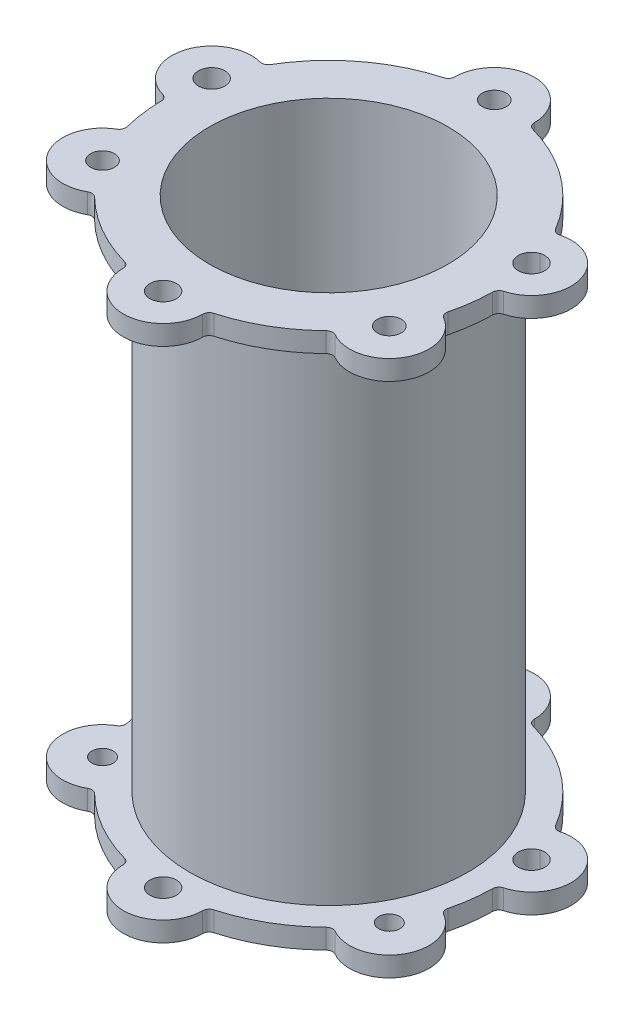
SolidWorks part; units mm, degrees
material "6061-T6 (SS)"
ref_plane "Front" through (0, 0, 0) normal (0, 0, 1) x (1, 0, 0)
ref_plane "Top" through (0, 0, 0) normal (0, 1, 0) x (1, 0, 0)
ref_plane "Right" through (0, 0, 0) normal (1, 0, 0) x (0, 0, -1)
sketch "Sketch1" plane through (0, 0, 0) normal (0, 1, 0) x (1, 0, 0)
  circle A0 centre (0, 0) radius 9
  circle A1 centre (0, 0) radius 10.5
  dimension "D1" = 18
  dimension "D2" = 21
extrude "Boss-Extrude1" add sketch "Sketch1" along normal blind 37.5
sketch "Sketch2" plane through (0, 37.5, 0) normal (0, 1, 0) x (1, 0, 0)
  line L0 (0, 10.5) -> (0, 12.5) construction
  line L1 (0, 0) -> (0, -12.5) construction
  line L2 (3, 0) -> (3, -12.5)
  line L3 (-3, 0) -> (-3, -12.5)
  line L4 (0, 0) -> (0, 12.5) construction
  line L7 (-3, 0) -> (-3, 12.5)
  line L10 (3, 0) -> (3, 12.5)
  line L11 (-1.5, -2.5981) -> (9.3253, -8.8481)
  line L12 (1.5, 2.5981) -> (12.3253, -3.6519)
  line L13 (0, 0) -> (10.8253, -6.25) construction
  line L14 (-1.5, 2.5981) -> (-12.3253, -3.6519)
  line L15 (1.5, -2.5981) -> (-9.3253, -8.8481)
  line L16 (0, 0) -> (-10.8253, -6.25) construction
  line L17 (0, 0) -> (-12.0741, 3.2352) construction
  line L18 (-0.7765, -2.8978) -> (-12.8505, 0.3375)
  line L19 (0.7765, 2.8978) -> (-11.2976, 6.133)
  line L20 (0, 36.7398) -> (0, -36.7398) construction
  line L21 (0, 0) -> (12.0741, 3.2352) construction
  line L22 (0.7765, -2.8978) -> (12.8505, 0.3375)
  line L23 (-0.7765, 2.8978) -> (11.2976, 6.133)
  circle A0 centre (0, 0) radius 9 construction
  circle A1 centre (0, 0) radius 9
  circle A2 centre (0, 0) radius 12.5
  circle A3 centre (0, 0) radius 10.5 construction
  arc A4 (3, 0) -> (-3, 0) centre (0, 0) ccw
  arc A5 (-3, -12.5) -> (3, -12.5) centre (0, -12.5) ccw
  circle A16 centre (0, -12.5) radius 1
  arc A22 (-3, 0) -> (3, 0) centre (0, 0) ccw
  arc A23 (3, 12.5) -> (-3, 12.5) centre (0, 12.5) ccw
  arc A25 (1.5, 2.5981) -> (-1.5, -2.5981) centre (0, 0) ccw
  arc A26 (9.3253, -8.8481) -> (12.3253, -3.6519) centre (10.8253, -6.25) ccw
  arc A28 (1.5, -2.5981) -> (-1.5, 2.5981) centre (0, 0) ccw
  arc A29 (-12.3253, -3.6519) -> (-9.3253, -8.8481) centre (-10.8253, -6.25) ccw
  arc A31 (-0.7765, -2.8978) -> (0.7765, 2.8978) centre (0, 0) ccw
  arc A32 (-11.2976, 6.133) -> (-12.8505, 0.3375) centre (-12.0741, 3.2352) ccw
  arc A33 (0.7765, -2.8978) -> (-0.7765, 2.8978) centre (0, 0) cw
  arc A34 (11.2976, 6.133) -> (12.8505, 0.3375) centre (12.0741, 3.2352) cw
  circle A35 centre (-12.0741, 3.2352) radius 1
  circle A36 centre (12.0741, 3.2352) radius 1
  point P8 (0, 11.5)
  point P10 (0, -6.25)
  point P19 (0, 6.25)
  point P29 (-6.037, 1.6176)
  point P31 (5.4127, -3.125)
  point P39 (-5.4127, -3.125)
  point P52 (6.037, 1.6176)
  point P55 (0, 0)
  dimension "D1" = 25
  dimension "D3" = 3
  dimension "D5" = 2
  dimension "D7" = 75
  dimension "D2" = 12.5
  dimension "D6" = 3
extrude "Boss-Extrude2" add sketch "Sketch2" along normal blind 1.5
ref_plane "Plane1" through (0, 18.75, 0) normal (0, -1, 0) x (-1, 0, 0)
fillet "Fillet1" radius 0.5 12 edges at (-3, 38.25, 12.1347) (3, 38.25, 12.1347) (9.0089, 38.25, 8.6654) (12.0089, 38.25, 3.4693) (12.4976, 38.25, -0.2429) (10.9447, 38.25, -6.0385) (3, 38.25, -12.1347) (-3, 38.25, -12.1347) (-10.9447, 38.25, -6.0385) (-12.4976, 38.25, -0.2429) (-12.0089, 38.25, 3.4693) (-9.0089, 38.25, 8.6654)
mirror "Mirror1" about plane through (0, 18.75, 0) normal (0, -1, 0) of "Boss-Extrude2", "Fillet1"
sketch "Sketch10" plane through (0, 0, 0) normal (0, 0, 1) x (1, 0, 0)
  line L0 (0, 0) -> (0, 10.55) construction
  circle A0 centre (0, 10.55) radius 7.65
  dimension "D2" = 15.3
  dimension "D1" = 10.55
extrude "Cut-Extrude1" cut sketch "Sketch10" against normal through all
sketch "Sketch11" plane through (0, -1.5, 0) normal (0, -1, 0) x (1, 0, 0)
  line L0 (0, 0) -> (0, -12.5) construction
  line L1 (0, 0) -> (-10.8253, 6.25) construction
  line L2 (0, 0) -> (10.8253, 6.25) construction
  dimension "D2" = 12.5
  dimension "D1" = 3
sketch "Sketch13" plane through (0, 39, 0) normal (0, 1, 0) x (1, 0, 0)
  line L0 (0, 0) -> (10.8253, -6.25) construction
  line L1 (0, 0) -> (-10.8253, -6.25) construction
  line L2 (0, 0) -> (0, 12.5) construction
  line L3 (0, 0) -> (10.8253, -6.25)
  line L4 (0, 0) -> (-10.8253, -6.25)
  line L5 (0, 0) -> (0, 12.5)
  circle A0 centre (0, 12.5) radius 0.9
  circle A1 centre (-10.8253, -6.25) radius 0.9
  circle A2 centre (10.8253, -6.25) radius 0.9
  dimension "D1" = 1.8
extrude "Cut-Extrude2" cut sketch "Sketch13" against normal up to surface (1.5 mm away) up to face at (0, 37.5, 10.5)
hole_wizard "M2x0.4 Tapped Hole3" positions "3DSketch2" profile "Sketch14" tap size "M2x0.4" standard "ANSI Metric"
sketch3d "3DSketch2"
  point P0 (10.8253, -1.5, 6.25)
  point P3 (0, -1.5, -12.5)
  point P6 (-10.8253, -1.5, 6.25)
sketch "Sketch14" plane through (10.8253, -1.5, 6.25) normal (1, 0, 0) x (0, 0, -1)
  line L0 (0, 0) -> (0, 1.9797)
  line L1 (0, 1.9797) -> (0.8, 1.499)
  line L2 (0.8, 1.499) -> (0.8, 0)
  line L5 (0.8, 0) -> (0, 0)
  line L10 (0, 1.9797) -> (-0.8, 1.499) construction
  line L11 (0, -6.35) -> (0, 107.95) construction
  dimension "Tap Drill Dia." = 1.6
  dimension "Tap Drill Depth" = 1.499
  dimension "Drill Angle" = 118
cosmetic thread "Hole Thread1" parameters "D1"=1.5, "D2"=2
cosmetic thread "Hole Thread2" parameters "D1"=1.5, "D2"=2
cosmetic thread "Hole Thread3" parameters "D1"=1.5, "D2"=2
